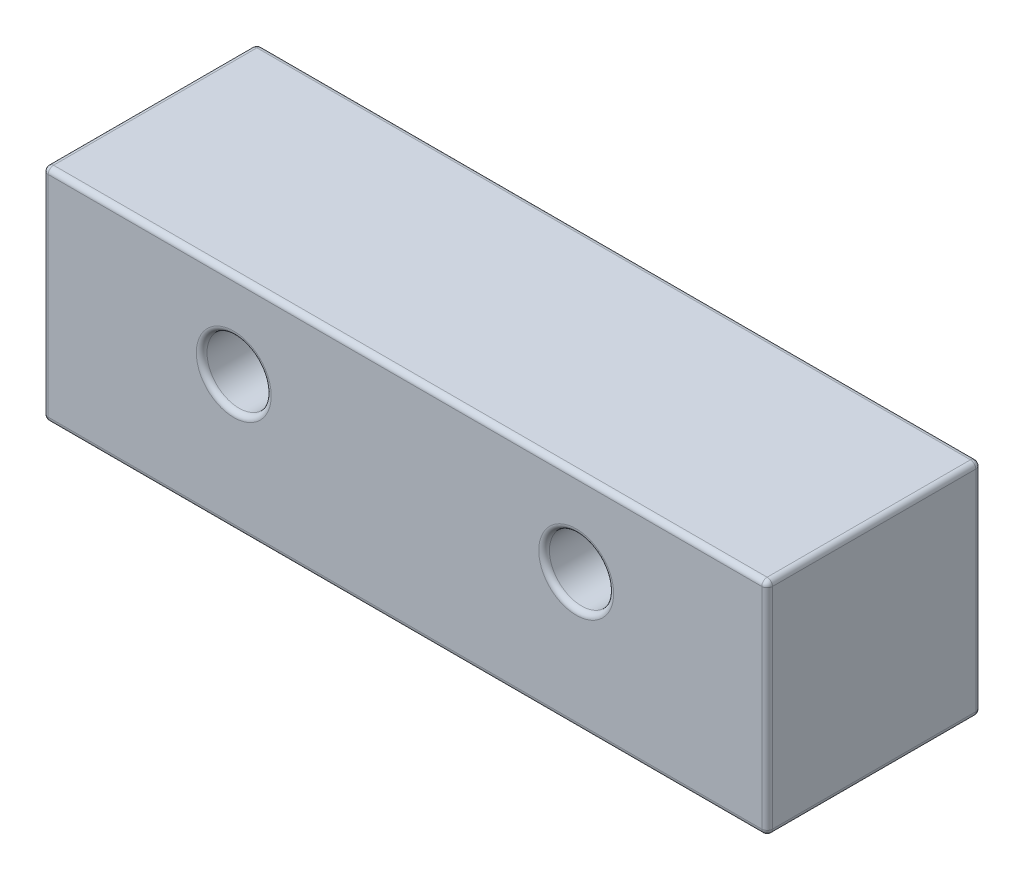
SolidWorks part; units mm, degrees
ref_plane "Front Plane" through (0, 0, 0) normal (0, 0, 1) x (1, 0, 0)
ref_plane "Top Plane" through (0, 0, 0) normal (0, 1, 0) x (1, 0, 0)
ref_plane "Right Plane" through (0, 0, 0) normal (1, 0, 0) x (0, 0, -1)
sketch "Sketch1" plane through (0, 0, 0) normal (0, 0, 1) x (1, 0, 0)
  line L0 (-67.6843, 20.6355) -> (-67.6843, 0)
  line L4 (0, 20.6355) -> (0, 0)
  line L5 (-67.6843, 0) -> (0, 0)
  line L6 (0, 20.6355) -> (-67.6843, 20.6355)
  circle A4 centre (-49.8421, 12.6355) radius 3
  circle A5 centre (-17.8421, 12.6355) radius 3
  dimension "D4" = 6
  dimension "D9" = 32
  dimension "D13" = 17.8421
  dimension "D2" = 8
  dimension "D3" = 17.8421
  dimension "D5" = 20.6355
  dimension "D6" = 67.6843
extrude "Boss-Extrude1" add sketch "Sketch1" along normal blind 20
fillet "Fillet1" radius 0.5 16 edges at (-14.8421, 12.6355, 0) (0, 10.3178, 0) (-67.6843, 10.3178, 0) (-46.8421, 12.6355, 0) (-67.6843, 0, 10) (0, 0, 10) (-33.8421, 0, 0) (-14.8421, 12.6355, 20) (-46.8421, 12.6355, 20) (-67.6843, 10.3178, 20) (0, 10.3178, 20) (-33.8421, 0, 20) (0, 20.6355, 10) (-33.8421, 20.6355, 20) (-67.6843, 20.6355, 10) (-33.8421, 20.6355, 0)
equation "\"D3@Sketch1\"=(\"D6@Sketch1\"-\"D9@Sketch1\")/2"
